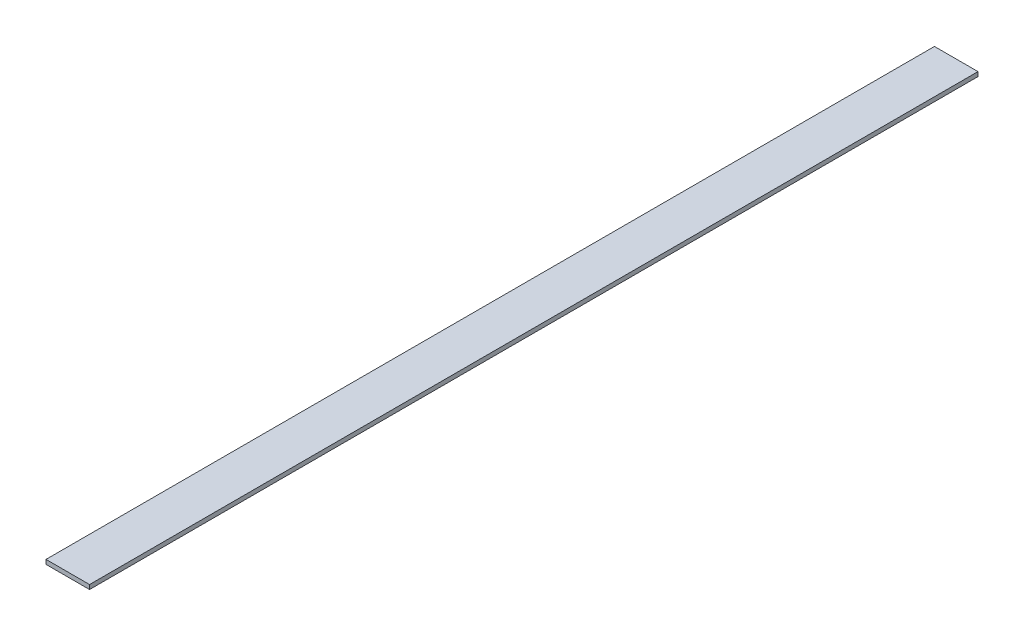
SolidWorks part; units mm, degrees
material "Acrylic (Medium-high impact)"
ref_plane "Front Plane" through (0, 0, 0) normal (0, 0, 1) x (1, 0, 0)
ref_plane "Top Plane" through (0, 0, 0) normal (0, 1, 0) x (1, 0, 0)
ref_plane "Right Plane" through (0, 0, 0) normal (1, 0, 0) x (0, 0, -1)
sketch "Sketch1" plane through (0, 0, 0) normal (0, 0, 1) x (1, 0, 0)
  line L1 (5, 0) -> (55, 0)
  line L5 (55, 5) -> (25, 5)
  line L9 (15, 5) -> (5, 5)
  line L12 (15, 5) -> (25, 5)
  line L13 (5, 5) -> (5, 0)
  line L14 (55, 5) -> (55, 0)
  dimension "D1" = 50
  dimension "D2" = 5
  dimension "D3" = 5
extrude "Boss-Extrude1" add sketch "Sketch1" along normal blind 1020
